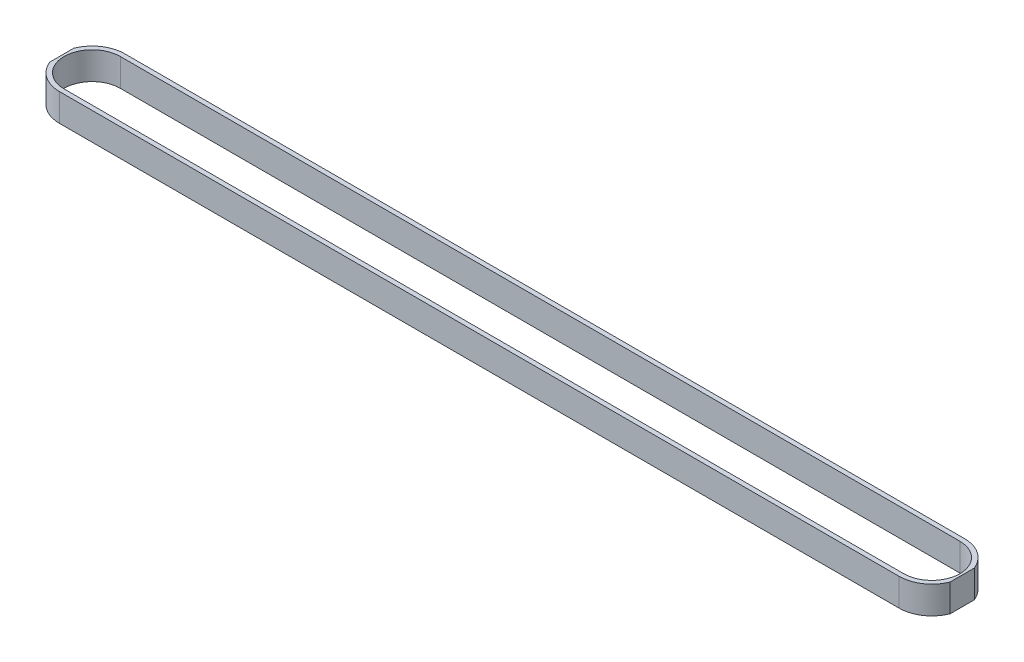
SolidWorks part; units mm, degrees
ref_plane "Front Plane" through (0, 0, 0) normal (0, 0, 1) x (1, 0, 0)
ref_plane "Top Plane" through (0, 0, 0) normal (0, 1, 0) x (1, 0, 0)
ref_plane "Right Plane" through (0, 0, 0) normal (1, 0, 0) x (0, 0, -1)
sketch "Sketch1" plane through (0, 0, 0) normal (0, 1, 0) x (1, 0, 0)
  line L0 (0, 0) -> (182.64, 0) construction
  line L1 (0, 6.1122) -> (182.64, 6.1122)
  line L2 (0, -6.1122) -> (182.64, -6.1122)
  line L3 (91.32, 0) -> (91.32, 14.2675) construction
  line L4 (0, 7.11) -> (182.64, 7.11)
  line L5 (0, -7.11) -> (182.64, -7.11)
  arc A0 (0, 6.1122) -> (0, -6.1122) centre (0, 0) ccw
  arc A1 (182.64, -6.1122) -> (182.64, 6.1122) centre (182.64, 0) ccw
  arc A2 (0, 7.11) -> (0, -7.11) centre (0, 0) ccw
  arc A3 (182.64, 7.11) -> (182.64, -7.11) centre (182.64, 0) cw
  dimension "D1" = 12.2244
  dimension "D3" = 7.11
  dimension "D2" = 182.64
extrude "Boss-Extrude1" add sketch "Sketch1" along normal blind 6
sketch "Sketch2" plane through (0, 6, 0) normal (0, 1, 0) x (1, 0, 0)
  line L0 (0, 0) -> (182.64, 0) construction
  line L1 (190.25, 7.5) -> (189.25, 7.5)
  line L2 (190.25, 7.5) -> (190.25, -7.5)
  line L3 (190.25, -7.5) -> (189.25, -7.5)
  line L4 (189.25, 7.5) -> (189.25, -7.5)
  line L5 (190.25, 7.5) -> (189.25, -7.5) construction
  line L6 (190.25, -7.5) -> (189.25, 7.5) construction
  line L7 (91.32, 0) -> (91.32, 44.7946) construction
  line L8 (-7.61, -7.5) -> (-6.61, -7.5)
  line L9 (-6.61, 7.5) -> (-6.61, -7.5)
  line L10 (-7.61, 7.5) -> (-6.61, 7.5)
  line L11 (-7.61, 7.5) -> (-7.61, -7.5)
  arc A0 (182.64, -7.11) -> (182.64, 7.11) centre (182.64, 0) ccw construction
  point P0 (189.75, 0)
  dimension "D1" = 1
  dimension "D2" = 15
extrude "Cut-Extrude1" cut sketch "Sketch2" against normal through all
